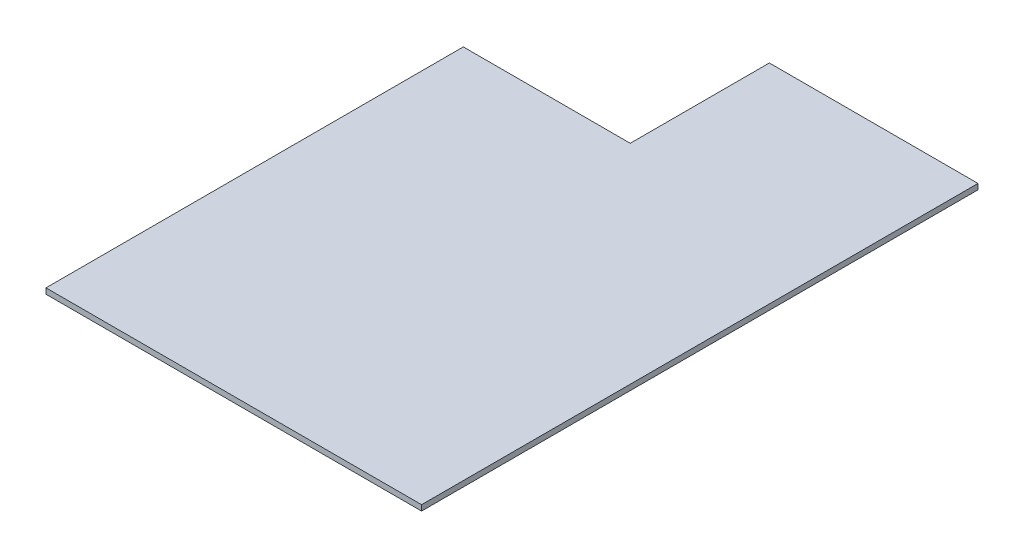
SolidWorks part; units mm, degrees
material "Corrugated Paper"
ref_plane "Front Plane" through (0, 0, 0) normal (0, 0, 1) x (1, 0, 0)
ref_plane "Top Plane" through (0, 0, 0) normal (0, 1, 0) x (1, 0, 0)
ref_plane "Right Plane" through (0, 0, 0) normal (1, 0, 0) x (0, 0, -1)
sketch "Sketch1" plane through (0, 0, 0) normal (0, 1, 0) x (1, 0, 0)
  line L0 (0, 0) -> (34.29, 0)
  line L1 (34.29, 0) -> (34.29, 50.8)
  line L2 (34.29, 50.8) -> (15.24, 50.8)
  line L3 (15.24, 50.8) -> (15.24, 38.1)
  line L4 (15.24, 38.1) -> (0, 38.1)
  line L5 (0, 38.1) -> (0, 0)
  dimension "D1" = 50.8
  dimension "D2" = 38.1
  dimension "D3" = 19.05
  dimension "D4" = 15.24
extrude "Boss-Extrude1" add sketch "Sketch1" along normal blind 0.508
